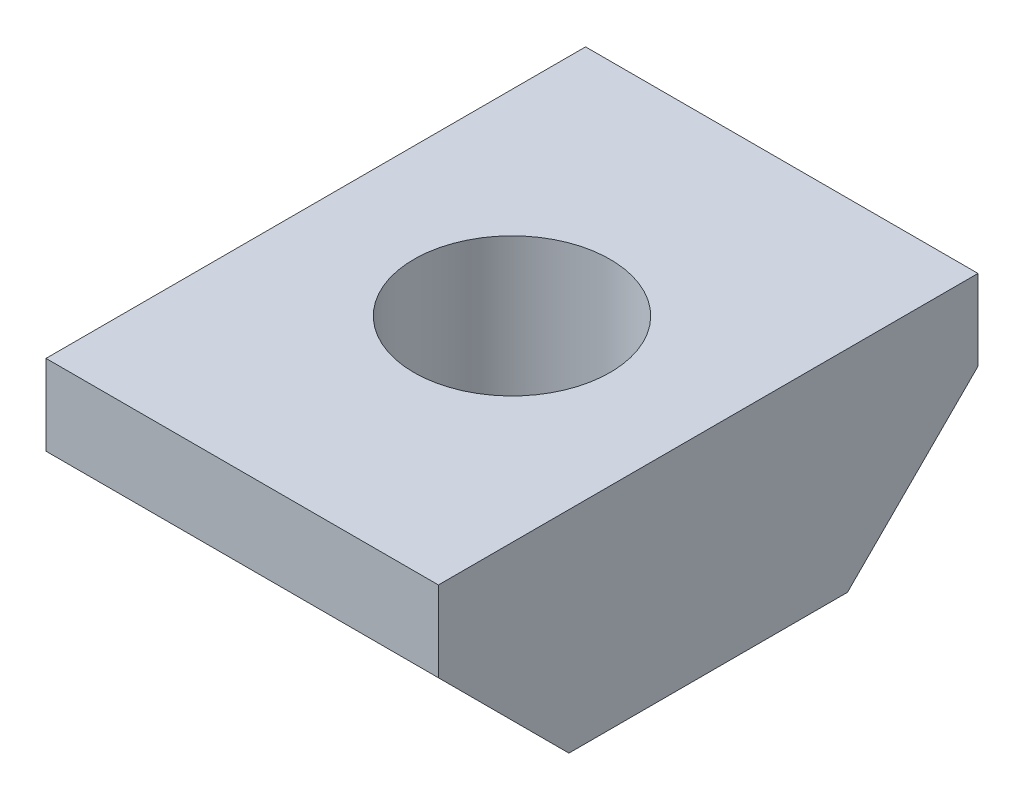
SolidWorks part; units mm, degrees
material "Plain Carbon Steel"
ref_plane "Front Plane" through (0, 0, 0) normal (0, 0, 1) x (1, 0, 0)
ref_plane "Top Plane" through (0, 0, 0) normal (0, 1, 0) x (1, 0, 0)
ref_plane "Right Plane" through (0, 0, 0) normal (1, 0, 0) x (0, 0, -1)
sketch "Sketch1" plane through (0, 0, 0) normal (1, 0, 0) x (0, 0, -1)
  line L0 (-2.8393, -4.3) -> (2.8393, -4.3)
  line L2 (-5.5, 0) -> (5.5, 0)
  line L6 (5.5, 0) -> (5.5, -1.6393)
  line L7 (5.5, -1.6393) -> (2.8393, -4.3)
  line L8 (0, 0) -> (0, -4.3) construction
  line L9 (-5.5, -1.6393) -> (-2.8393, -4.3)
  line L10 (-5.5, 0) -> (-5.5, -1.6393)
  dimension "D1" = 5.5
  dimension "D2" = 4.3
  dimension "D3" = 3.7627
  dimension "D4" = 5.6787
extrude "Boss-Extrude1" add sketch "Sketch1" along normal blind 8
sketch "Sketch7" plane through (0, 0, 0) normal (0, 1, 0) x (1, 0, 0)
  line L0 (0, 5.5) -> (0, -5.5) construction
  line L1 (8, -5.5) -> (0, -5.5) construction
  circle A0 centre (4, 0) radius 2
  dimension "D1" = 4
  dimension "D2" = 4
  dimension "D3" = 5.5
extrude "Cut-Extrude1" cut sketch "Sketch7" against normal up to surface (4.3 mm away) up to face at (4, -4.3, 0)
